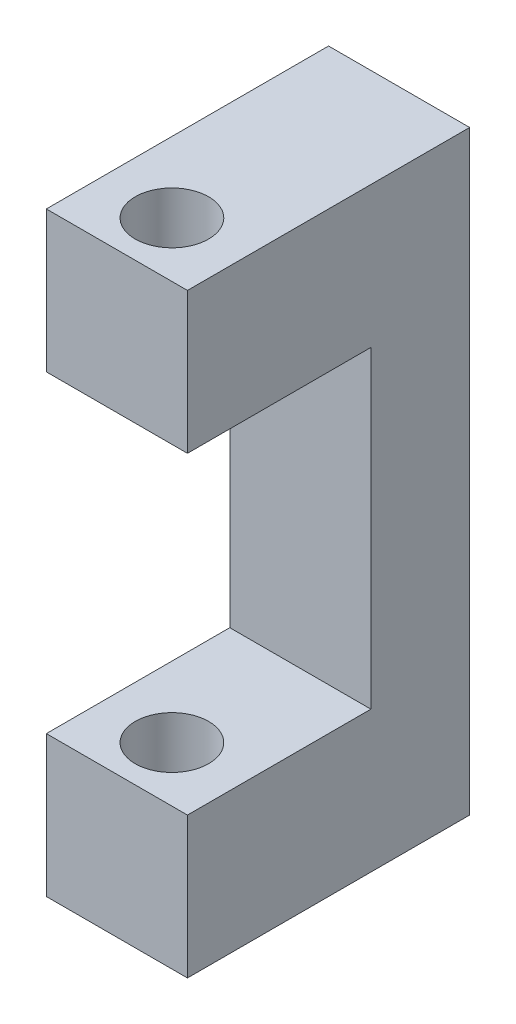
SolidWorks part; units mm, degrees
ref_plane "Front Plane" through (0, 0, 0) normal (1, 0, 0) x (0, 1, 0)
ref_plane "Top Plane" through (0, 0, 0) normal (0, 0, 1) x (0, 1, 0)
ref_plane "Right Plane" through (0, 0, 0) normal (0, 1, 0) x (-1, 0, 0)
sketch "Sketch1" plane through (0, 0, 0) normal (0, 0, 1) x (0, 1, 0)
  line L0 (-58.6336, 10) -> (-58.6336, 5)
  line L1 (-75.7336, 10) -> (-41.5336, 10)
  line L2 (-75.7336, 10) -> (-75.7336, 0)
  line L3 (-75.7336, 0) -> (-41.5336, 0)
  line L4 (-41.5336, 10) -> (-41.5336, 0)
  line L5 (-70.6336, 5) -> (-69.7336, 5)
  line L6 (-46.6336, 5) -> (-47.5336, 5)
  circle A0 centre (-72.7336, 5) radius 2.1
  circle A2 centre (-44.5336, 5) radius 2.1
  point P10 (-70.6336, 5)
  point P13 (-46.6336, 5)
  dimension "D1" = 5
  dimension "D4" = 4.2
  dimension "D2" = 3
  dimension "D3" = 5
  dimension "D5" = 3
  dimension "D6" = 22.2
extrude "Boss-Extrude1" add sketch "Sketch1" along normal blind 3
sketch "Sketch2" plane through (0, 0, 3) normal (0, 0, 1) x (1, 0, 0)
  line L0 (0, -75.7336) -> (0, -41.5336) construction
  line L1 (-10, -75.7336) -> (0, -75.7336)
  line L2 (-10, -75.7336) -> (-10, -69.7336)
  line L3 (-10, -69.7336) -> (0, -69.7336)
  line L4 (0, -75.7336) -> (0, -69.7336)
  line L5 (-10, -58.6336) -> (-7.0692, -58.6336)
  line L6 (-10, -75.7336) -> (-10, -41.5336) construction
  line L7 (0, -41.5336) -> (0, -47.5336)
  line L8 (-10, -47.5336) -> (0, -47.5336)
  line L9 (-10, -41.5336) -> (-10, -47.5336)
  line L10 (-10, -41.5336) -> (0, -41.5336)
  circle M3 centre (-5, -72.7336) radius 2.1
  line M4 (0, -41.5336) -> (-10, -41.5336)
  line M5 (-10, -41.5336) -> (-10, -75.7336)
  line M6 (-10, -75.7336) -> (0, -75.7336)
  line M7 (0, -75.7336) -> (0, -41.5336)
  circle M8 centre (-5, -44.5336) radius 2.1
  dimension "D1" = 6
extrude "Boss-Extrude2" add sketch "Sketch2" along normal blind 3 contours L8 M5 M7 M4 M8 | L3 M5 M6 M7 M3
sketch "Sketch4" plane through (0, 0, 6) normal (0, 0, 1) x (1, 0, 0)
  line L1 (-10, -41.5336) -> (0, -41.5336)
  line L2 (-10, -41.5336) -> (-10, -47.5336)
  line L3 (-10, -47.5336) -> (0, -47.5336)
  line L4 (0, -41.5336) -> (0, -47.5336)
  line L5 (0, -69.7336) -> (-10, -69.7336)
  line L6 (0, -69.7336) -> (0, -75.7336)
  line L7 (0, -75.7336) -> (-10, -75.7336)
  line L8 (-10, -69.7336) -> (-10, -75.7336)
extrude "Boss-Extrude3" add sketch "Sketch4" along normal blind 12
sketch "Sketch5" plane through (0, -75.7336, 0) normal (0, -1, 0) x (1, 0, 0)
  line L0 (-10, 0) -> (0, 0) construction
  line L1 (0, 18) -> (0, 0) construction
  circle A0 centre (-5, 14.1) radius 2.6
  dimension "D1" = 5.2
  dimension "D2" = 14.1
  dimension "D3" = 5
extrude "Cut-Extrude1" cut sketch "Sketch5" against normal blind 45 contours A0
sketch "Sketch6" plane through (0, 0, 3) normal (0, 0, 1) x (1, 0, 0)
  line L1 (-10, -47.5336) -> (0, -47.5336)
  line L2 (-10, -47.5336) -> (-10, -69.7336)
  line L3 (-10, -69.7336) -> (0, -69.7336)
  line L4 (0, -47.5336) -> (0, -69.7336)
extrude "Boss-Extrude4" add sketch "Sketch6" along normal blind 2
sketch "Sketch7" plane through (0, -75.7336, 0) normal (0, -1, 0) x (1, 0, 0)
  line L1 (-10, 18) -> (0, 18)
  line L2 (-10, 18) -> (-10, 0)
  line L3 (-10, 0) -> (0, 0)
  line L4 (0, 18) -> (0, 0)
  circle A0 centre (-5, 14.1) radius 2.6
extrude "Boss-Extrude5" add sketch "Sketch7" along normal blind 4
sketch "Sketch8" plane through (0, -41.5336, 0) normal (0, 1, 0) x (-1, 0, 0)
  line L1 (0, 18) -> (10, 18)
  line L2 (0, 18) -> (0, 0)
  line L3 (0, 0) -> (10, 0)
  line L4 (10, 18) -> (10, 0)
  circle A0 centre (5, 14.1) radius 2.6
  circle A1 centre (5, 14.1) radius 2.6 construction
extrude "Boss-Extrude6" add sketch "Sketch8" along normal blind 4
sketch "Sketch10" plane through (0, 0, 0) normal (0, 0, -1) x (1, 0, 0)
  line L1 (-10, 79.7336) -> (0, 79.7336)
  line L2 (-10, 79.7336) -> (-10, 37.5336)
  line L3 (-10, 37.5336) -> (0, 37.5336)
  line L4 (0, 79.7336) -> (0, 37.5336)
  circle A0 centre (-5, 72.7336) radius 2.1
  circle A1 centre (-5, 44.5336) radius 2.1
  circle A2 centre (-5, 72.7336) radius 2.1 construction
  circle A3 centre (-5, 44.5336) radius 2.1 construction
extrude "Boss-Extrude7" add sketch "Sketch10" along normal blind 2
